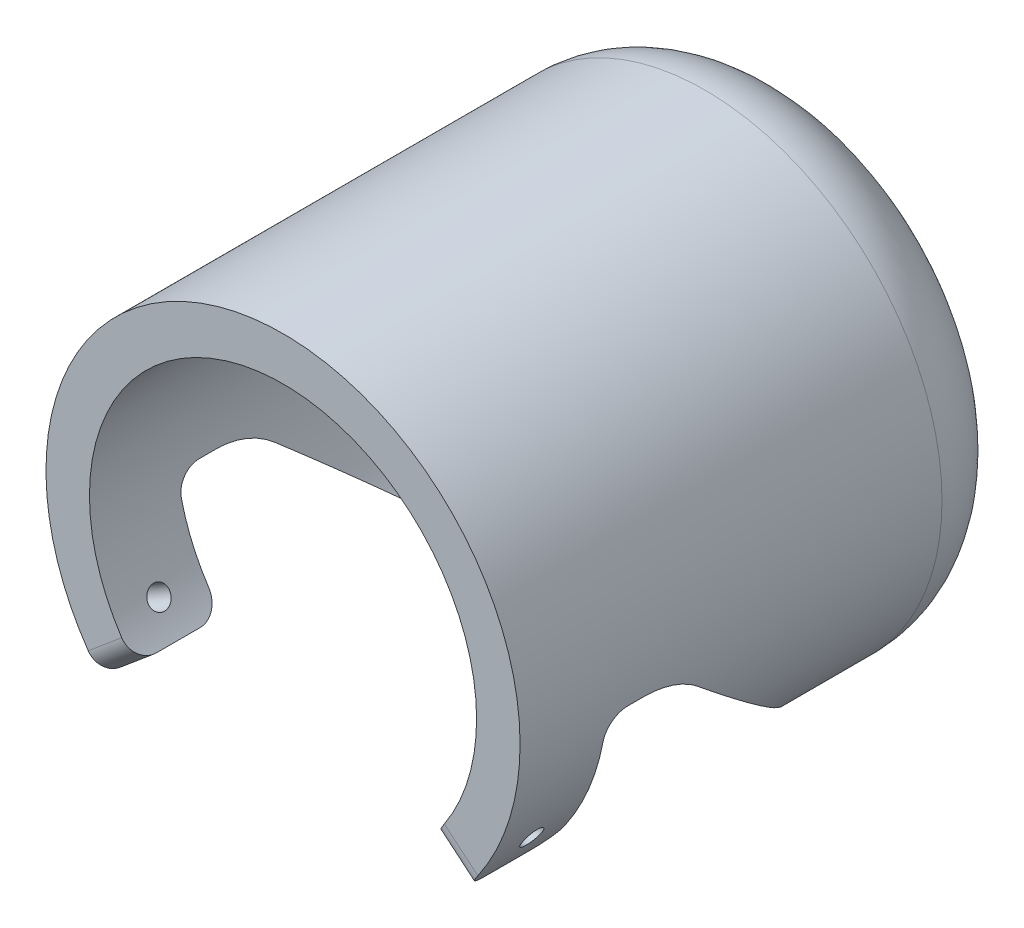
SolidWorks part; units mm, degrees
material "硅橡胶板 "
ref_plane "前视" through (0, 0, 0) normal (0, 0, 1) x (1, 0, 0)
ref_plane "上视" through (0, 0, 0) normal (0, 1, 0) x (1, 0, 0)
ref_plane "右视" through (0, 0, 0) normal (1, 0, 0) x (0, 0, -1)
sketch "草图1" plane through (0, 0, 0) normal (0, 0, 1) x (1, 0, 0)
  circle A0 centre (0, 0) radius 54.5
  circle A1 centre (0, 0) radius 51.5 construction
  dimension "D1" = 109
  dimension "D2" = 3
extrude "凸台-拉伸1" add sketch "草图1" along normal mid plane 117
fillet "圆角1" radius 20 1 edges at (54.5, 0, -58.5)
shell "抽壳1" thickness 10
sketch "草图2" plane through (0, 0, 0) normal (1, 0, 0) x (0, 0, -1)
  line L0 (0, 0) -> (-70.7678, 0) construction
  line L1 (-38.5, -54.5) -> (-38.5, -10)
  line L2 (-58.5, -54.5) -> (38.5, -54.5) construction
  line L3 (-33.5, -5) -> (-29.7712, -5)
  line L4 (-16.9155, -9.6791) -> (36.5, -54.5)
  line L5 (-58.5, 54.5) -> (-58.5, -54.5) construction
  line L6 (-38.5, -54.5) -> (36.5, -54.5)
  arc A0 (-29.7712, -5) -> (-16.9155, -9.6791) centre (-29.7712, -25) cw
  arc A1 (-38.5, -10) -> (-33.5, -5) centre (-33.5, -10) cw
  point P13 (-22.4918, -5)
  point P16 (-38.5, -5)
  point P20 (-38.5, -5)
  dimension "D5" = 20
  dimension "D6" = 5
  dimension "D1" = 20
  dimension "D2" = 5
  dimension "D3" = 95
  dimension "D4" = 40
  dimension "D7" = 0
extrude "切除-拉伸1" cut sketch "草图2" against normal through all both and the other way through all
sketch "草图3" plane through (0, 0, 58.5) normal (0, 0, 1) x (1, 0, 0)
  line L0 (0, 0) -> (0, -75.8405) construction
  line L1 (34.089, -28.604) -> (41.7494, -35.0319)
  line L2 (-34.089, -28.604) -> (-41.7494, -35.0319)
  circle A0 centre (0, 0) radius 54.5 construction
  circle A1 centre (0, 0) radius 44.5 construction
  arc A2 (-41.7494, -35.0319) -> (41.7494, -35.0319) centre (0, 0) ccw
  arc A3 (-34.089, -28.604) -> (34.089, -28.604) centre (0, 0) ccw
  dimension "D1" = 100
extrude "切除-拉伸2" cut sketch "草图3" against normal up to next
sketch "草图4" plane through (0, 0, 58.5) normal (0, 0, 1) x (1, 0, 0)
  circle A0 centre (0, 0) radius 30
  dimension "D1" = 60
extrude "切除-拉伸3" cut sketch "草图4" against normal through all
fillet "圆角2" radius 5 4 edges at (-37.9192, -31.818, 38.5) (-37.9192, -31.818, 58.5) (37.9192, -31.818, 58.5) (37.9192, -31.818, 38.5)
ref_plane "基准面2" through (0, 0, 48.5) normal (0, 0, 1) x (1, 0, 0)
sketch "草图6" plane through (0, 0, 48.5) normal (0, 0, 1) x (1, 0, 0)
  line L0 (0, -69.3583) -> (0, 0) construction
  line L1 (0, 0) -> (80.8275, -46.6658) construction
  line L2 (0, 0) -> (1.25, 2.1651)
  line L3 (1.25, 2.1651) -> (68.0545, -36.4045)
  line L4 (68.0545, -36.4045) -> (66.8045, -38.5696)
  line L5 (66.8045, -38.5696) -> (0, 0)
  dimension "D1" = 60
  dimension "D2" = 5
revolve "切除-旋转1" cut sketch "草图6" angle 360 about L1
mirror "镜向2" about plane through (0, 0, 0) normal (1, 0, 0) of "切除-旋转1"
